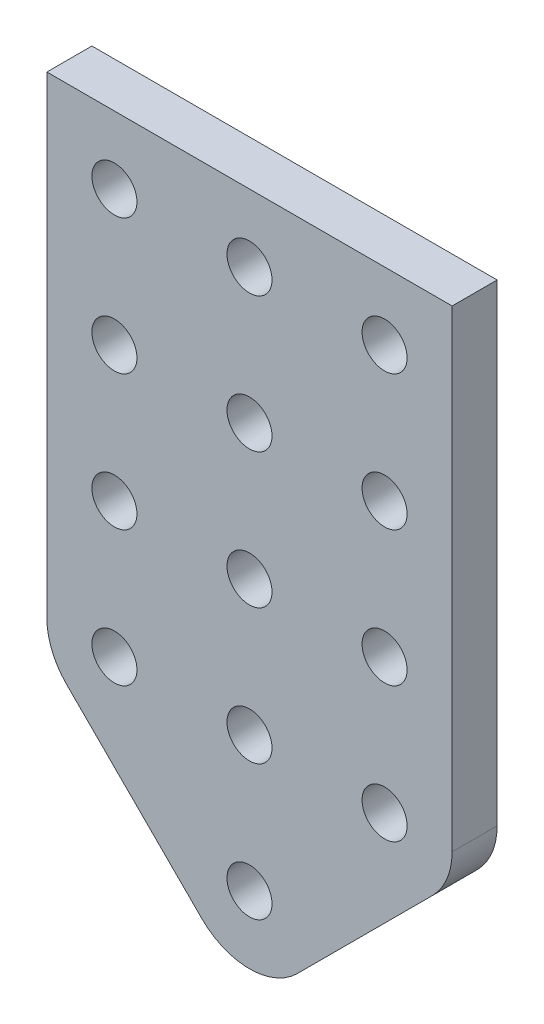
SolidWorks part; units mm, degrees
ref_plane "Alzado" through (0, 0, 0) normal (0, 0, 1) x (1, 0, 0)
ref_plane "Planta" through (0, 0, 0) normal (0, 1, 0) x (1, 0, 0)
ref_plane "Vista lateral" through (0, 0, 0) normal (1, 0, 0) x (0, 0, -1)
sketch "Model" plane through (0, 0, 0) normal (0, 0, 1) x (1, 0, 0)
  line L0 (174.2271, 213.1787) -> (174.2271, 204.1787)
  line L1 (174.2271, 213.1787) -> (174.2271, 235.6787)
  line L2 (201.2271, 235.6787) -> (201.2271, 204.1787)
  line L3 (190.909, 191.9967) -> (199.909, 200.9967)
  line L4 (184.5451, 191.9967) -> (175.5451, 200.9967)
  line L5 (201.2271, 235.6787) -> (174.2271, 235.6787)
  circle A0 centre (187.7271, 204.1787) radius 1.5
  circle A1 centre (178.7271, 204.1787) radius 1.5
  circle A2 centre (187.7271, 213.1787) radius 1.5
  circle A3 centre (178.7271, 213.1787) radius 1.5
  circle A4 centre (196.7271, 213.1787) radius 1.5
  circle A5 centre (187.7271, 195.1787) radius 1.5
  circle A6 centre (196.7271, 204.1787) radius 1.5
  arc A7 (184.5451, 191.9967) -> (190.909, 191.9967) centre (187.7271, 195.1787) ccw
  arc A8 (199.909, 200.9967) -> (201.2271, 204.1787) centre (196.7271, 204.1787) ccw
  arc A9 (174.2271, 204.1787) -> (175.5451, 200.9967) centre (178.7271, 204.1787) ccw
  circle A10 centre (187.7271, 222.1787) radius 1.5
  circle A11 centre (178.7271, 222.1787) radius 1.5
  circle A12 centre (196.7271, 222.1787) radius 1.5
  circle A13 centre (187.7271, 231.1787) radius 1.5
  circle A14 centre (178.7271, 231.1787) radius 1.5
  circle A15 centre (196.7271, 231.1787) radius 1.5
extrude "Saliente-Extruir1" add sketch "Model" along normal blind 3
